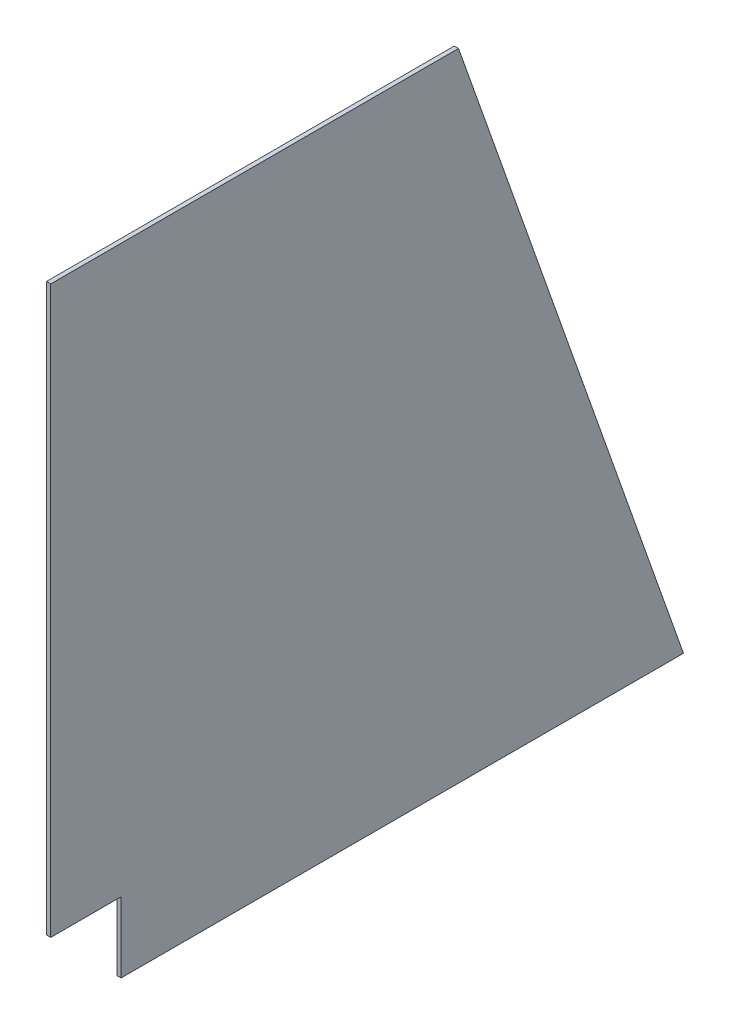
SolidWorks part; units mm, degrees
ref_plane "Front" through (0, 0, 0) normal (0, 0, 1) x (1, 0, 0)
ref_plane "Top" through (0, 0, 0) normal (0, 1, 0) x (1, 0, 0)
ref_plane "Right" through (0, 0, 0) normal (1, 0, 0) x (0, 0, -1)
sketch "Sketch1" plane through (0, 0, 0) normal (1, 0, 0) x (0, 0, -1)
  line L0 (31.6697, 625.5737) -> (191.6697, 173.0253)
  line L15 (-258.3303, 625.5737) -> (-258.3303, 173.0253)
  line L17 (-258.3303, 625.5737) -> (31.6697, 625.5737)
  line L18 (191.6697, 173.0253) -> (-258.3303, 173.0253)
  circle A0 centre (31.6697, 625.5737) radius 480 construction
  dimension "D3" = 450
  dimension "D1" = 480
  dimension "D2" = 452.5483
  dimension "D4" = 290
extrude "Boss-Extrude1" add sketch "Sketch1" along normal blind 3
sketch "Sketch2" plane through (0, 0, 0) normal (-1, 0, 0) x (0, 0, 1)
  line L1 (258.3303, 173.0253) -> (208.3303, 173.0253)
  line L2 (258.3303, 173.0253) -> (258.3303, 223.0253)
  line L3 (258.3303, 223.0253) -> (208.3303, 223.0253)
  line L4 (208.3303, 173.0253) -> (208.3303, 223.0253)
  dimension "D1" = 50
  dimension "D2" = 50
extrude "Cut-Extrude1" cut sketch "Sketch2" against normal blind 10
